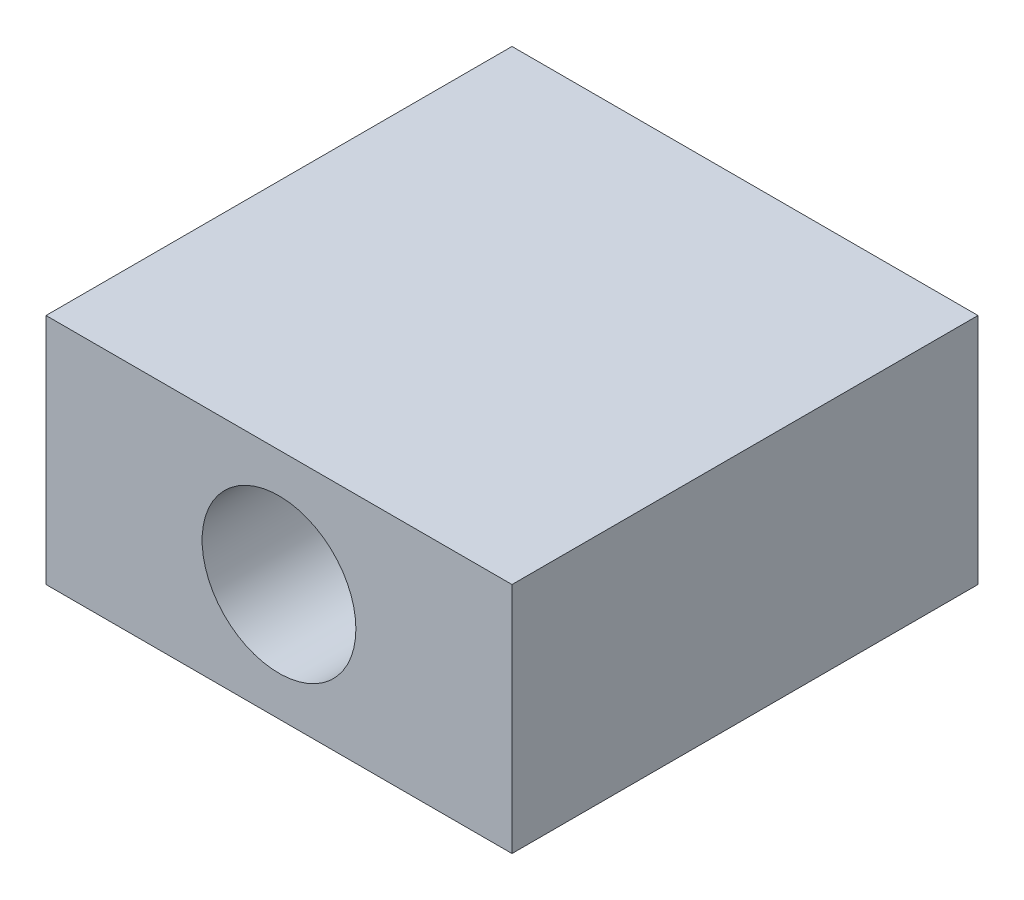
SolidWorks part; units mm, degrees
ref_plane "前视基准面" through (0, 0, 0) normal (0, 0, 1) x (1, 0, 0)
ref_plane "上视基准面" through (0, 0, 0) normal (0, 1, 0) x (1, 0, 0)
ref_plane "右视基准面" through (0, 0, 0) normal (1, 0, 0) x (0, 0, -1)
other "Configuration Table"
sketch "草图1" plane through (0, 0, 0) normal (0, 0, 1) x (1, 0, 0)
  line L1 (0, 0) -> (20, 0)
  line L2 (0, 0) -> (0, 10)
  line L3 (0, 10) -> (20, 10)
  line L4 (20, 0) -> (20, 10)
  circle A0 centre (10, 5) radius 3.3
extrude "End_stop_20x10x20" add sketch "草图1" along normal blind 20
